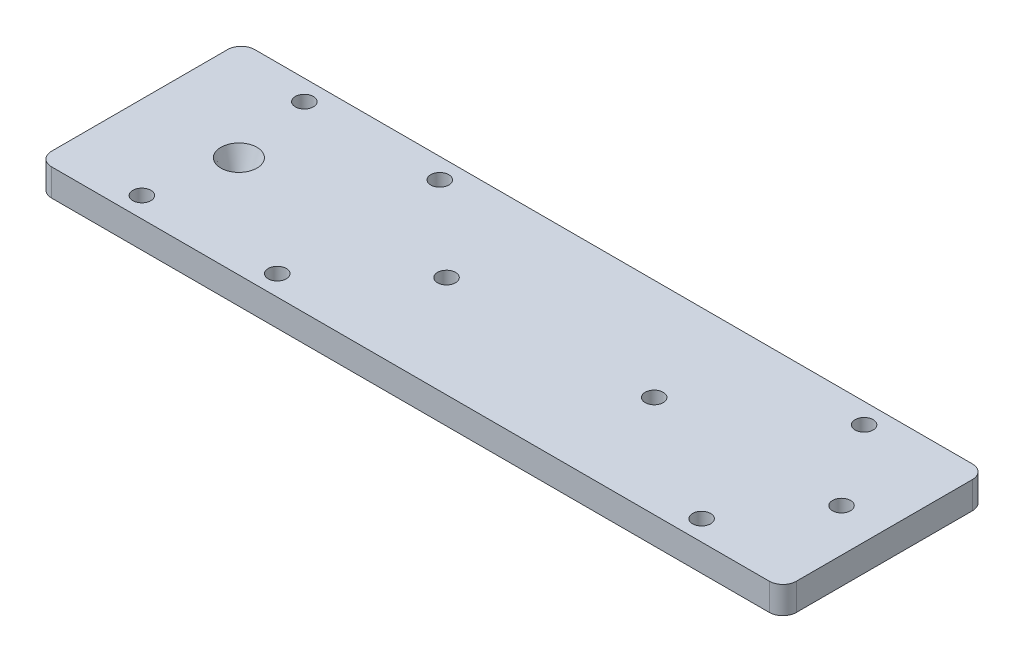
SolidWorks part; units mm, degrees
material "Alumina"
ref_plane "Front Plane" through (0, 0, 0) normal (0, 0, 1) x (1, 0, 0)
ref_plane "Top Plane" through (0, 0, 0) normal (0, 1, 0) x (1, 0, 0)
ref_plane "Right Plane" through (0, 0, 0) normal (1, 0, 0) x (0, 0, -1)
sketch "Sketch1" plane through (0, 0, 0) normal (0, 1, 0) x (1, 0, 0)
  line L0 (0, 0) -> (50000, 0) construction
  line L1 (-79.5, 22.5) -> (79.5, 22.5)
  line L2 (-82.5, 19.5) -> (-82.5, -19.5)
  line L3 (-79.5, -22.5) -> (79.5, -22.5)
  line L4 (82.5, 19.5) -> (82.5, -19.5)
  line L5 (-82.5, 22.5) -> (82.5, -22.5) construction
  line L6 (-82.5, -22.5) -> (82.5, 22.5) construction
  line L7 (0, 0) -> (0, 50000) construction
  line L8 (-82.5, 18) -> (82.5, 18) construction
  arc A0 (79.5, 22.5) -> (82.5, 19.5) centre (79.5, 19.5) cw
  arc A1 (79.5, -22.5) -> (82.5, -19.5) centre (79.5, -19.5) ccw
  arc A2 (-82.5, -19.5) -> (-79.5, -22.5) centre (-79.5, -19.5) ccw
  arc A3 (-79.5, 22.5) -> (-82.5, 19.5) centre (-79.5, 19.5) ccw
  circle A4 centre (-64, 18) radius 2
  circle A5 centre (-34, 18) radius 2
  circle A6 centre (60, 18) radius 2
  circle A7 centre (-60.5, 0) radius 2
  circle A8 centre (-14.5, 0) radius 2
  circle A9 centre (31.5, 0) radius 2
  circle A10 centre (73, 0) radius 2
  circle A11 centre (60, -18) radius 2
  circle A12 centre (-34, -18) radius 2
  circle A13 centre (-64, -18) radius 2
  point P0 (0, 0)
  dimension "D3" = 3
  dimension "D5" = 4
  dimension "D1" = 165
  dimension "D2" = 45
  dimension "D4" = 18
  dimension "D6" = 18.5
  dimension "D7" = 30
  dimension "D8" = 22.5
  dimension "D9" = 46
  dimension "22" = 22
  dimension "D10" = 46
  dimension "9.5" = 9.5
extrude "Boss-Extrude1" add sketch "Sketch1" along normal mid plane 6
sketch "Sketch7" plane through (0, 0, 0) normal (0, 0, 1) x (1, 0, 0)
  line L0 (-58.5, -3) -> (-56.5, 3)
  line L1 (-79.5, -3) -> (79.5, -3) construction
  line L2 (-62.5, -3) -> (-58.5, -3) construction
  line L3 (-79.5, 3) -> (79.5, 3) construction
  line L4 (-82.5, 3) -> (-82.5, -3) construction
  line L5 (-60.5, 0) -> (-60.5, -50000) construction
  line L7 (-58.5, -3) -> (-58.5, 3)
  line L8 (-58.5, 3) -> (-62.5, 3) construction
  line L9 (-58.5, 3) -> (-56.5, 3)
  dimension "D1" = 24
  dimension "D2" = 22
  dimension "D3" = 4
revolve "Cut-Revolve1" cut sketch "Sketch7" angle 360 about L5
